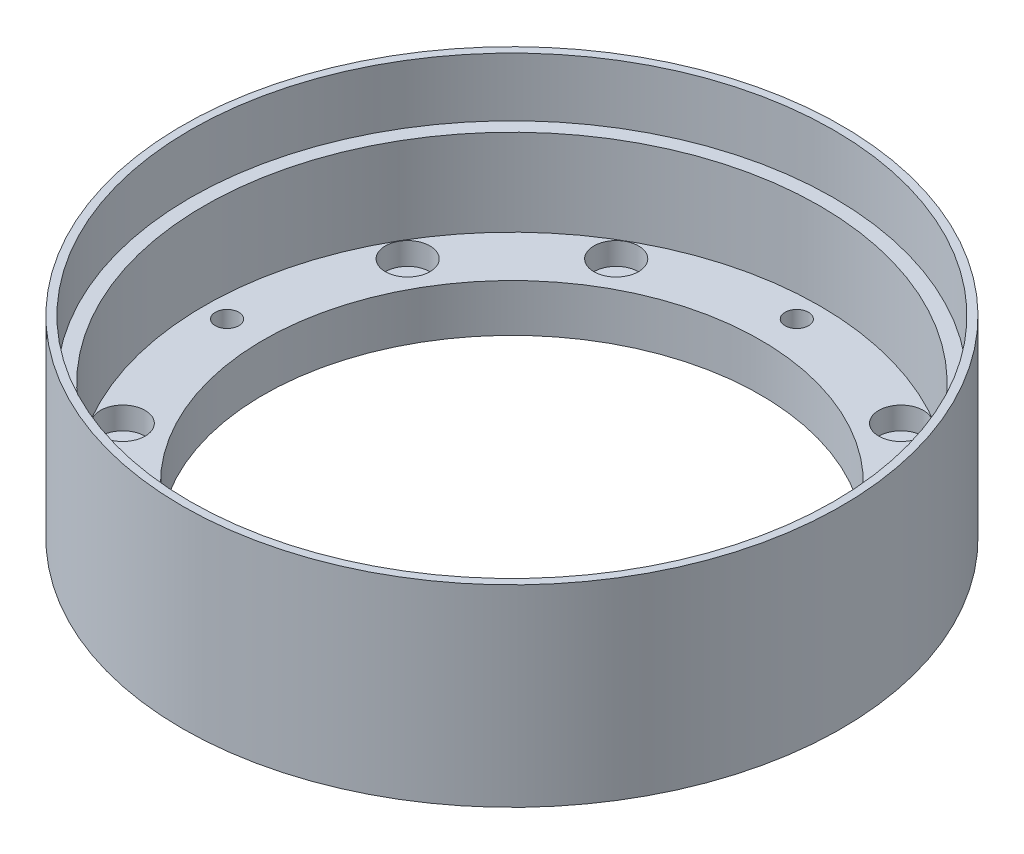
SolidWorks part; units mm, degrees
ref_plane "Front Plane" through (0, 0, 0) normal (0, 0, 1) x (1, 0, 0)
ref_plane "Top Plane" through (0, 0, 0) normal (0, 1, 0) x (1, 0, 0)
ref_plane "Right Plane" through (0, 0, 0) normal (1, 0, 0) x (0, 0, -1)
other "Configuration Table"
sketch "草图1" plane through (0, 0, 0) normal (0, 1, 0) x (1, 0, 0)
  circle A0 centre (0, 0) radius 59
  dimension "D1" = 118
extrude "凸台-拉伸1" add sketch "草图1" along normal blind 34.5
sketch "草图2" plane through (0, 34.5, 0) normal (0, 1, 0) x (1, 0, 0)
  circle A0 centre (0, 0) radius 57.6
extrude "切除-拉伸1" cut sketch "草图2" against normal blind 10.5
sketch "草图3" plane through (0, 24, 0) normal (0, 1, 0) x (1, 0, 0)
  circle A0 centre (0, 0) radius 55.1
extrude "切除-拉伸2" cut sketch "草图3" against normal blind 15.5
sketch "草图4" plane through (0, 8.5, 0) normal (0, 1, 0) x (1, 0, 0)
  circle A0 centre (0, 0) radius 44.5
  dimension "D1" = 89
extrude "切除-拉伸3" cut sketch "草图4" against normal through all
sketch "草图9" plane through (0, 8.5, 0) normal (0, 1, 0) x (1, 0, 0)
  line L0 (0, 0) -> (-44.1673, 25.5) construction
  circle A0 centre (-44.1673, 25.5) radius 4
  circle A1 centre (-25.5, 44.1673) radius 4
  circle A3 centre (25.5, 44.1673) radius 4
  circle A4 centre (44.1673, 25.5) radius 4
  circle A6 centre (44.1673, -25.5) radius 4
  circle A7 centre (25.5, -44.1673) radius 4
  circle A9 centre (-25.5, -44.1673) radius 4
  circle A10 centre (-44.1673, -25.5) radius 4
  circle A12 centre (0, 51) radius 4 [skipped]
  circle A13 centre (-51, 0) radius 4 [skipped]
  circle A14 centre (51, 0) radius 4 [skipped]
  circle A15 centre (0, -51) radius 4 [skipped]
  point P28 (0, 0)
  dimension "D1" = 12
extrude "切除-拉伸7" cut sketch "草图9" against normal blind 4
sketch "草图10" plane through (0, 8.5, 0) normal (0, 1, 0) x (1, 0, 0)
  line L0 (0, 0) -> (0, 51) construction
  circle A0 centre (0, 51) radius 2.1
  circle A1 centre (51, 0) radius 2.1
  circle A2 centre (0, -51) radius 2.1
  circle A3 centre (-51, 0) radius 2.1
  point P13 (0, 0)
  dimension "D1" = 4
extrude "切除-拉伸8" cut sketch "草图10" against normal through all
sketch "草图11" plane through (0, 0, 0) normal (0, -1, 0) x (1, 0, 0)
  line L0 (0, 51) -> (0, 0) construction
  circle A0 centre (0, 51) radius 3.75
  circle A1 centre (51, 0) radius 3.75
  circle A2 centre (0, -51) radius 3.75
  circle A3 centre (-51, 0) radius 3.75
  point P14 (0, 0)
  dimension "D1" = 4
extrude "切除-拉伸9" cut sketch "草图11" against normal blind 5
sketch "草图12" plane through (0, 0, 0) normal (0, -1, 0) x (-1, 0, 0)
  line L1 (0, 0) -> (0, 59) construction
  line L3 (-0.5, 58) -> (0.5, 58)
  line L4 (0.5, 58) -> (0.5, 59)
  line L5 (0.5, 59) -> (-0.5, 59)
  line L6 (-0.5, 59) -> (-0.5, 58)
  line L7 (0, 0) -> (12.1167, 0) construction
  line L8 (-0.5, -59) -> (-0.5, -58)
  line L9 (0.5, -59) -> (-0.5, -59)
  line L10 (0.5, -58) -> (0.5, -59)
  line L11 (-0.5, -58) -> (0.5, -58)
  line L12 (0, -59) -> (0, -58.5)
  circle A0 centre (0, 0) radius 59 construction
  point P11 (0, 58)
  point P19 (0, -58)
extrude "切除-拉伸10" [suppressed] cut sketch "草图12" against normal blind 1
